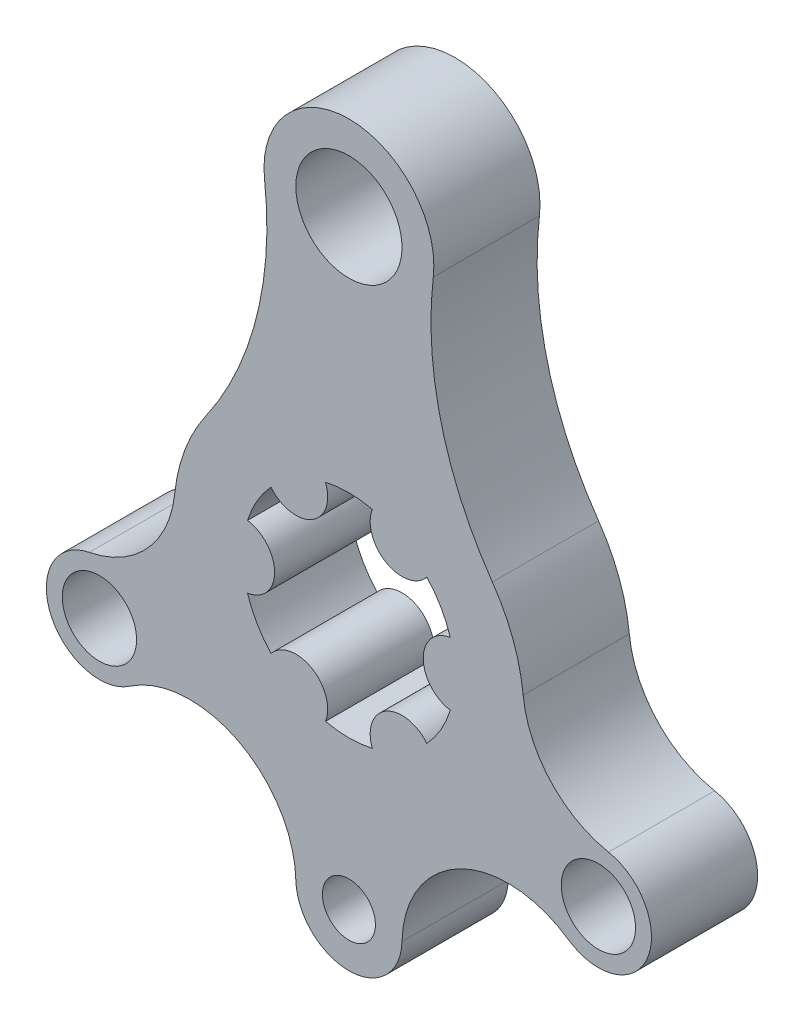
SolidWorks part; units mm, degrees
ref_plane "Front Plane" through (0, 0, 0) normal (0, 0, 1) x (1, 0, 0)
ref_plane "Top Plane" through (0, 0, 0) normal (0, 1, 0) x (1, 0, 0)
ref_plane "Right Plane" through (0, 0, 0) normal (1, 0, 0) x (0, 0, -1)
sketch "Sketch2" plane through (0, 0, 0) normal (0, 0, 1) x (1, 0, 0)
  line L0 (0, 0) -> (0, 129.1396) construction
  line L1 (0, 0) -> (212.6204, 0) construction
  arc A0 (32.8251, 3.3933) -> (27.0298, 18.9312) centre (0, 0) ccw
  arc A1 (15.8903, 63.1292) -> (-15.8903, 63.1292) centre (0, 65) ccw
  arc A2 (-48.9064, -14.1834) -> (-41.3305, -32.2375) centre (-47, -24) ccw
  arc A3 (-9.9972, -48.2375) -> (9.9972, -48.2375) centre (0, -48) ccw
  arc A4 (-27.0298, 18.9312) -> (-15.8903, 63.1292) centre (-79.4513, 55.6462) ccw
  arc A5 (27.0298, 18.9312) -> (15.8903, 63.1292) centre (79.4513, 55.6462) cw
  arc A6 (-48.9064, -14.1834) -> (-32.8251, 3.3933) centre (-52.7191, 5.4498) ccw
  arc A7 (-9.9972, -48.2375) -> (-41.3305, -32.2375) centre (-29.9915, -48.7126) ccw
  arc A8 (9.9972, -48.2375) -> (41.3305, -32.2375) centre (29.9915, -48.7126) cw
  arc A9 (48.9064, -14.1834) -> (41.3305, -32.2375) centre (47, -24) cw
  arc A10 (48.9064, -14.1834) -> (32.8251, 3.3933) centre (52.7191, 5.4498) cw
  arc A11 (-27.0298, 18.9312) -> (-32.8251, 3.3933) centre (0, 0) ccw
  dimension "D1" = 32
  dimension "D2" = 66
  dimension "D4" = 128
  dimension "D5" = 20
  dimension "D6" = 20
  dimension "D10" = 40
  dimension "D3" = 65
  dimension "D7" = 47
  dimension "D8" = 24
  dimension "D9" = 24
extrude "Boss-Extrude1" add sketch "Sketch2" against normal blind 20 contours A7 A2 A6 A11 A4 A1 A5 A0 A10 A9 A8 A3
sketch "Sketch3" plane through (0, 0, -20) normal (0, 0, -1) x (-1, 0, 0)
  circle A0 centre (0, 65) radius 10
  circle A1 centre (47, -24) radius 7
  circle A2 centre (0, -48) radius 5
  circle A3 centre (-47, -24) radius 7
  arc A4 (-14.6874, 13.575) -> (-19.1, 5.9321) centre (0, 0) ccw
  arc A5 (19.1, 5.9321) -> (19.1, -5.9321) centre (20, 0) ccw
  arc A6 (14.6874, -13.575) -> (4.4126, -19.5071) centre (10, -17.3205) ccw
  arc A7 (-4.4126, -19.5071) -> (-14.6874, -13.575) centre (-10, -17.3205) ccw
  arc A8 (-19.1, -5.9321) -> (-19.1, 5.9321) centre (-20, 0) ccw
  arc A9 (-14.6874, 13.575) -> (-4.4126, 19.5071) centre (-10, 17.3205) ccw
  arc A10 (4.4126, 19.5071) -> (14.6874, 13.575) centre (10, 17.3205) ccw
  arc A11 (4.4126, 19.5071) -> (-4.4126, 19.5071) centre (0, 0) ccw
  arc A12 (19.1, 5.9321) -> (14.6874, 13.575) centre (0, 0) ccw
  arc A13 (14.6874, -13.575) -> (19.1, -5.9321) centre (0, 0) ccw
  arc A14 (-4.4126, -19.5071) -> (4.4126, -19.5071) centre (0, 0) ccw
  arc A15 (-19.1, -5.9321) -> (-14.6874, -13.575) centre (0, 0) ccw
  point P17 (0, 0)
  point P18 (0, -5.3599)
  point P29 (0, 0)
  dimension "D2" = 12
  dimension "D3" = 40
  dimension "D4" = 20
  dimension "D5" = 14
  dimension "D6" = 10
  dimension "D7" = 14
  dimension "D1" = 6
extrude "Cut-Extrude1" cut sketch "Sketch3" against normal through all
